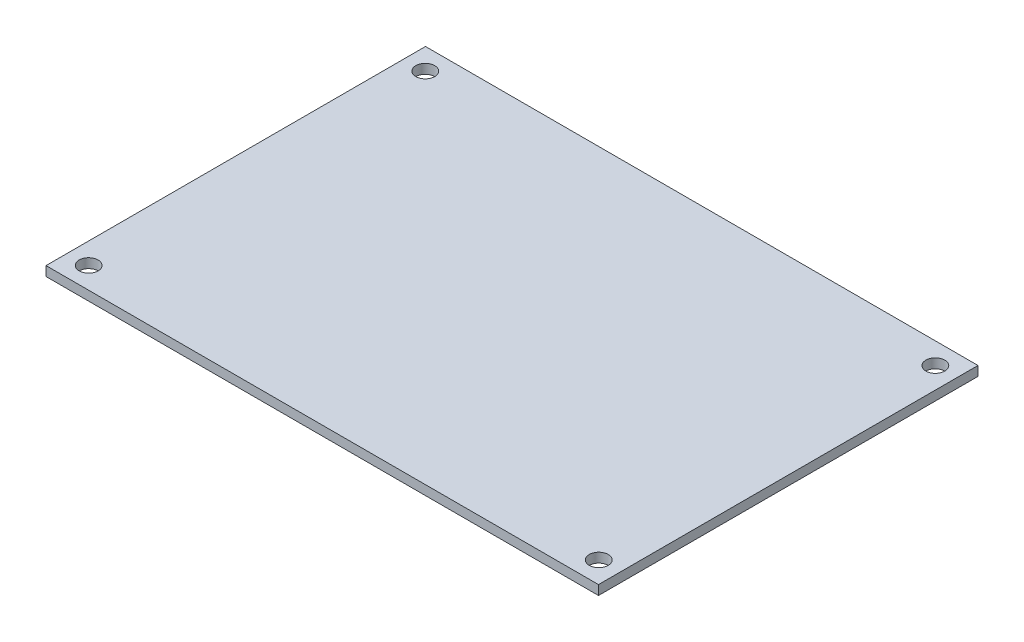
SolidWorks part; units mm, degrees
ref_plane "Front Plane" through (0, 0, 0) normal (0, 0, 1) x (1, 0, 0)
ref_plane "Top Plane" through (0, 0, 0) normal (0, 1, 0) x (1, 0, 0)
ref_plane "Right Plane" through (0, 0, 0) normal (1, 0, 0) x (0, 0, -1)
sketch "Sketch3" plane through (0, 0, 0) normal (0, 1, 0) x (1, 0, 0)
  line L1 (-43.675, 30) -> (43.675, 30)
  line L2 (-43.675, 30) -> (-43.675, -30)
  line L3 (-43.675, -30) -> (43.675, -30)
  line L4 (43.675, 30) -> (43.675, -30)
  line L5 (-43.675, 30) -> (43.675, -30) construction
  line L6 (-43.675, -30) -> (43.675, 30) construction
  point P0 (0, 0)
  dimension "D1" = 60
  dimension "D2" = 87.35
extrude "Boss-Extrude1" add sketch "Sketch3" along normal blind 1.5
sketch "Sketch4" plane through (0, 1.5, 0) normal (0, 1, 0) x (1, 0, 0)
  line L1 (-40.3225, 26.608) -> (40.3225, 26.608) construction
  line L2 (-40.3225, 26.608) -> (-40.3225, -26.608) construction
  line L3 (-40.3225, -26.608) -> (40.3225, -26.608) construction
  line L4 (40.3225, 26.608) -> (40.3225, -26.608) construction
  line L5 (-40.3225, 26.608) -> (40.3225, -26.608) construction
  line L6 (-40.3225, -26.608) -> (40.3225, 26.608) construction
  circle A0 centre (-40.3225, 26.608) radius 1.5
  circle A1 centre (40.3225, 26.608) radius 1.5
  circle A2 centre (40.3225, -26.608) radius 1.5
  circle A3 centre (-40.3225, -26.608) radius 1.5
  point P0 (0, 0)
  dimension "D3" = 3
  dimension "D1" = 53.216
  dimension "D2" = 80.645
extrude "Cut-Extrude1" cut sketch "Sketch4" against normal blind 1.5
sketch "Sketch5" plane through (0, 1.5, 0) normal (0, 1, 0) x (1, 0, 0)
  circle A0 centre (20.6375, 0) radius 17.25
  circle A2 centre (40.3225, -26.608) radius 1.5 construction
  dimension "D1" = 19.685
  dimension "D2" = 34.5
extrude "Boss-Extrude2" [suppressed] add sketch "Sketch5" along normal blind 24
